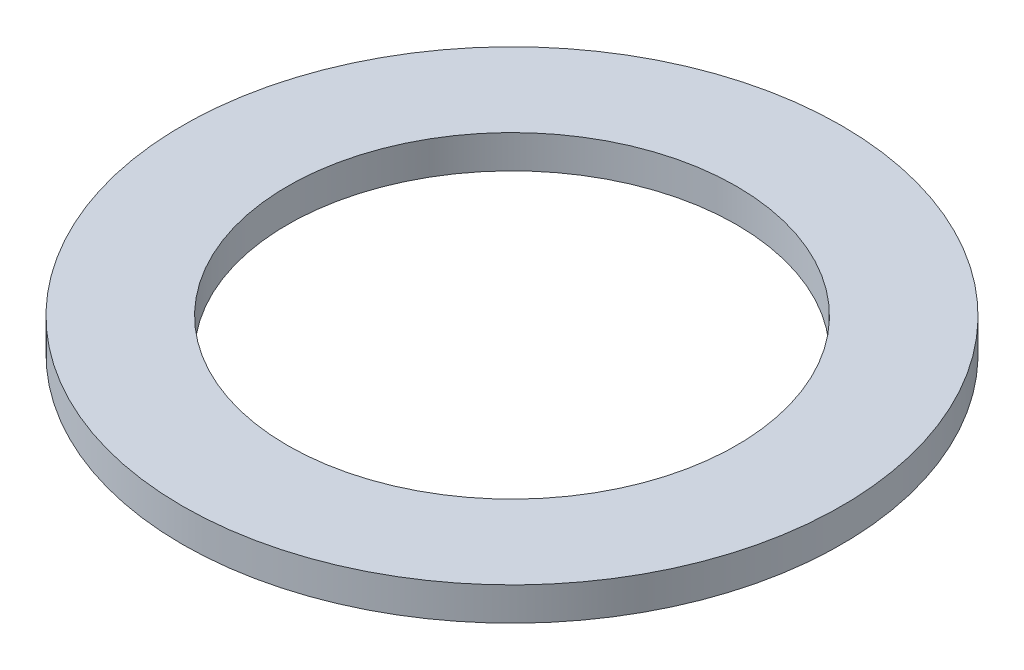
SolidWorks part; units mm, degrees
ref_plane "Front Plane" through (0, 0, 0) normal (0, 0, 1) x (1, 0, 0)
ref_plane "Top Plane" through (0, 0, 0) normal (0, 1, 0) x (1, 0, 0)
ref_plane "Right Plane" through (0, 0, 0) normal (1, 0, 0) x (0, 0, -1)
sketch "Sketch1" plane through (0, 0, 0) normal (0, 1, 0) x (1, 0, 0)
  circle A0 centre (0, 0) radius 20.3
  circle A1 centre (0, 0) radius 29.8
  dimension "D1" = 40.6
  dimension "D2" = 59.6
extrude "Boss-Extrude1" add sketch "Sketch1" along normal blind 3
